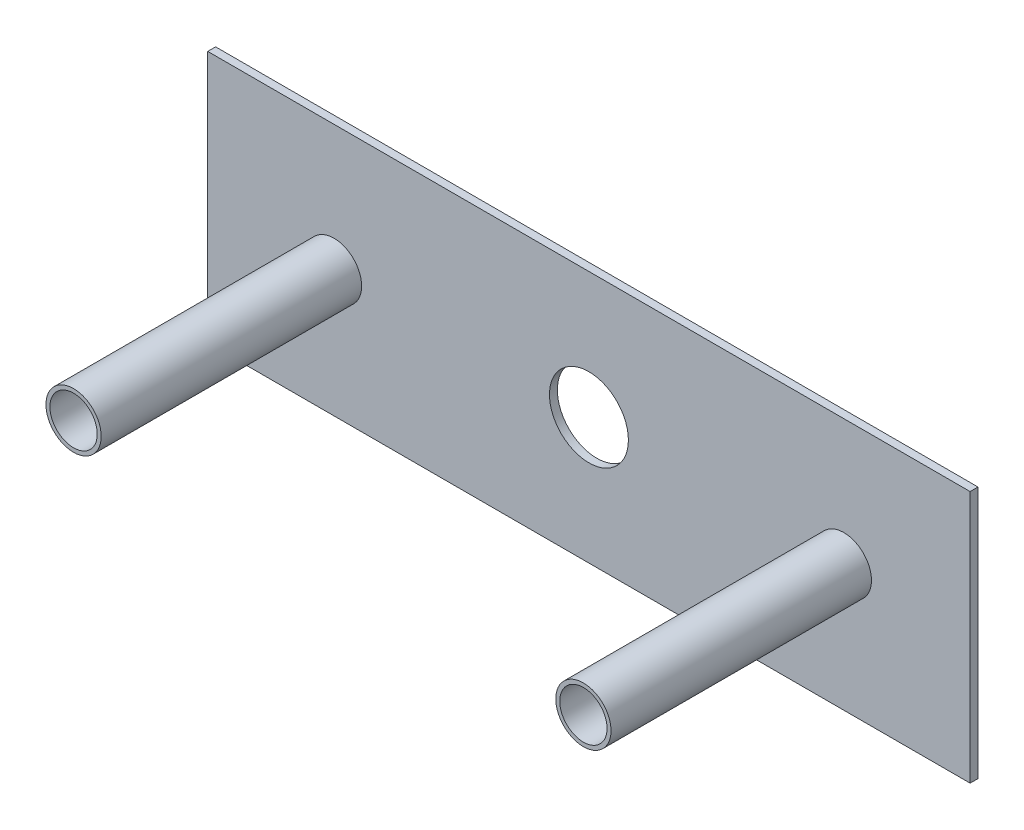
SolidWorks part; units mm, degrees
ref_plane "Plan de face" through (0, 0, 0) normal (0, 0, 1) x (1, 0, 0)
ref_plane "Plan de dessus" through (0, 0, 0) normal (0, 1, 0) x (1, 0, 0)
ref_plane "Plan de droite" through (0, 0, 0) normal (1, 0, 0) x (0, 0, -1)
sketch "Esquisse1" plane through (0, 0, 0) normal (0, 0, 1) x (1, 0, 0)
  line L1 (-47.6288, 18.2599) -> (48.9712, 18.2599)
  line L2 (-47.6288, 18.2599) -> (-47.6288, -13.7401)
  line L3 (-47.6288, -13.7401) -> (48.9712, -13.7401)
  line L4 (48.9712, 18.2599) -> (48.9712, -13.7401)
  dimension "D1" = 96.6
  dimension "D2" = 32
extrude "Boss.-Extru.1" add sketch "Esquisse1" along normal blind 1
sketch "Esquisse6" plane through (0, 0, 1) normal (0, 0, 1) x (1, 0, 0)
  line L0 (-47.6288, 18.2599) -> (-47.6288, -13.7401) construction
  line L3 (48.9712, 18.2599) -> (-47.6288, 18.2599) construction
  line L4 (48.9712, -13.7401) -> (48.9712, 18.2599) construction
  circle A0 centre (-31.6288, 2.2599) radius 3.5
  circle A1 centre (32.9712, 2.2599) radius 3.5
  dimension "D1" = 7
  dimension "D4" = 7
  dimension "D2" = 16
  dimension "D3" = 16
  dimension "D5" = 16
  dimension "D6" = 16
extrude "Boss.-Extru.2" add sketch "Esquisse6" along normal blind 33
sketch "Esquisse7" plane through (0, 0, 34) normal (0, 0, 1) x (1, 0, 0)
  line L1 (-47.6288, 18.2599) -> (-47.6288, -13.7401) construction
  line L3 (48.9712, 18.2599) -> (-47.6288, 18.2599) construction
  line L4 (48.9712, -13.7401) -> (48.9712, 18.2599) construction
  line L5 (-47.6288, -13.7401) -> (48.9712, -13.7401) construction
  circle A0 centre (-31.6288, 2.2599) radius 3
  circle A1 centre (32.9712, 2.2599) radius 3
  circle A2 centre (0.6712, 2.2599) radius 5
  dimension "D1" = 6
  dimension "D4" = 6
  dimension "D7" = 10
  dimension "D2" = 16
  dimension "D3" = 16
  dimension "D5" = 16
  dimension "D6" = 16
  dimension "D8" = 16
  dimension "D9" = 48.3
extrude "Enlèv. mat.-Extru.1" cut sketch "Esquisse7" against normal through all
